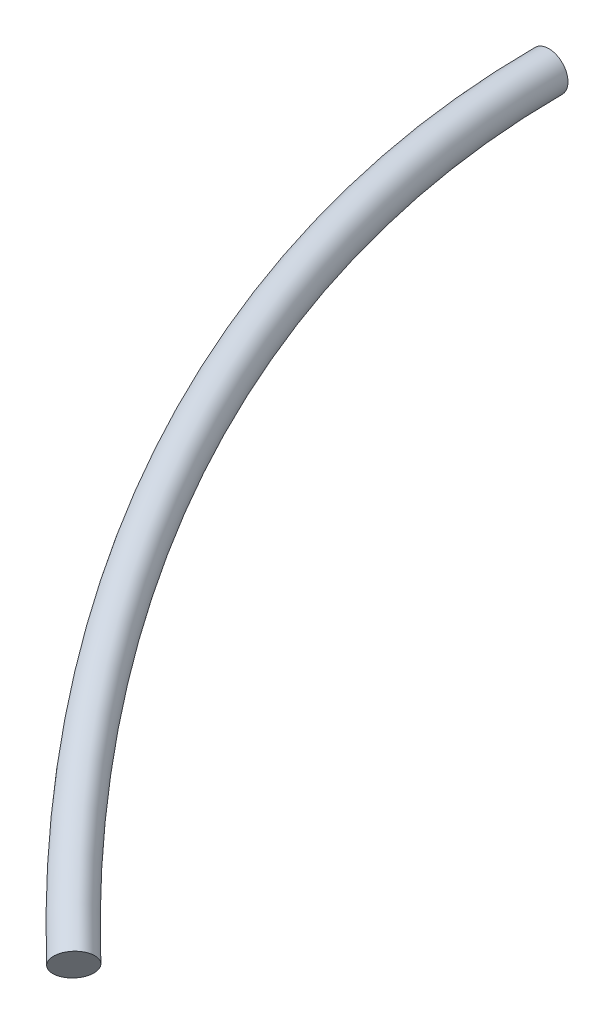
SolidWorks part; units mm, degrees
ref_plane "Front" through (0, 0, 0) normal (0, 0, 1) x (1, 0, 0)
ref_plane "Top" through (0, 0, 0) normal (0, 1, 0) x (1, 0, 0)
ref_plane "Right" through (0, 0, 0) normal (1, 0, 0) x (0, 0, -1)
sketch "Sketch1" plane through (0, 0, 0) normal (0, 0, 1) x (1, 0, 0)
  circle A0 centre (-3888.0393, -13523.7473) radius 50.8
ref_plane "Plane1" through (-7294.5573, -11330.6693, 0) normal (0.5413, 0.8408, 0) x (-0.4626, 0.2978, 0.8351)
sketch "Sketch2" plane through (-7294.5573, -11330.6693, 0) normal (0.5413, 0.8408, 0) x (-0.4626, 0.2978, 0.8351)
  line L0 (-2228.9716, 3383.1408) -> (-829.2419, 4305.3482) construction
  line L1 (-1023.0928, 5407.7924) -> (-904.8886, 6776.8507) construction
  arc A0 (-2228.9716, 3383.1408) -> (-1023.0928, 5407.7924) centre (-3716.0976, 5640.3057) ccw
  point P3 (-1050.2305, 5193.6625)
  point P5 (-1302.1407, 4424.1029)
  point P6 (-1770.6827, 3763.6869)
  dimension "D1" = 2438.4
  dimension "D2" = 215.9
  dimension "D3" = 812.8
  dimension "D4" = 812.8
sweep "Sweep1" add profiles "Sketch1" path "Sketch2"
